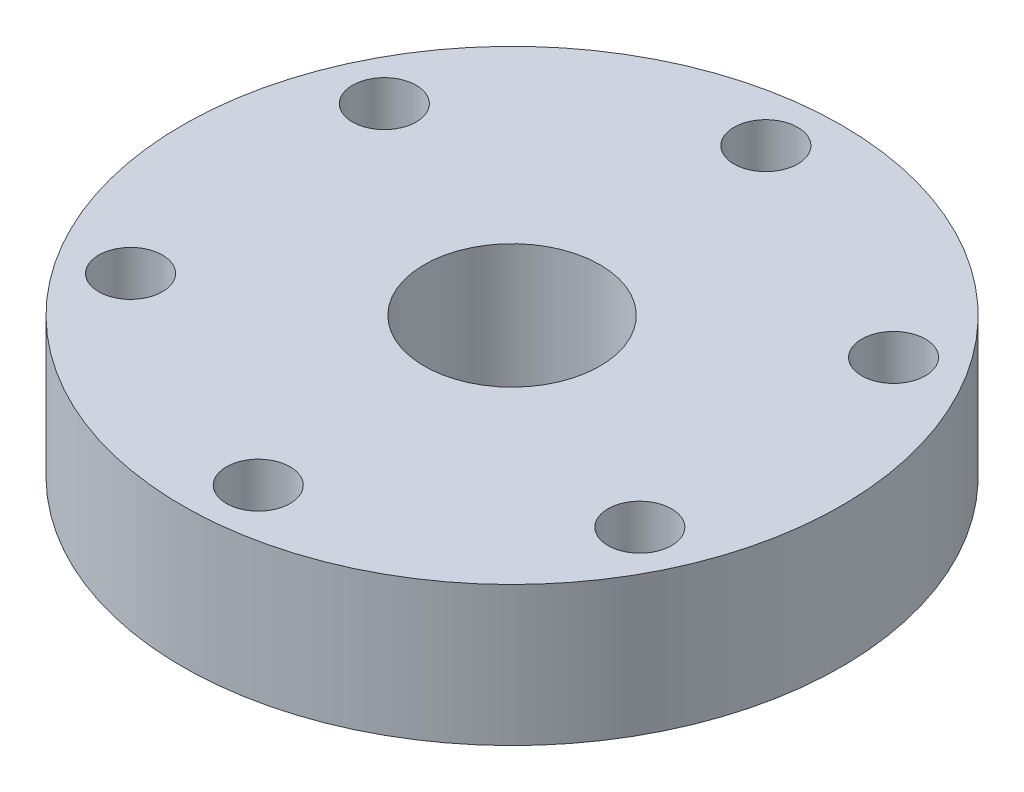
SolidWorks part; units mm, degrees
material "Aleación 6061"
ref_plane "Alzado" through (0, 0, 0) normal (0, 0, 1) x (1, 0, 0)
ref_plane "Planta" through (0, 0, 0) normal (0, 1, 0) x (1, 0, 0)
ref_plane "Vista lateral" through (0, 0, 0) normal (1, 0, 0) x (0, 0, -1)
sketch "Croquis1" plane through (0, 0, 0) normal (0, 1, 0) x (1, 0, 0)
  circle A0 centre (152.4, -336.55) radius 15
  dimension "D1" = 30
  dimension "D2" = 152.4
  dimension "D3" = 336.55
extrude "Disco" add sketch "Croquis1" along normal blind 6.35 from offset 3.175
sketch "Croquis2" plane through (0, 0, 0) normal (0, 1, 0) x (1, 0, 0)
  circle A0 centre (163.654, -341.9904) radius 1.45
  circle A1 centre (153.3155, -349.0164) radius 1.45
  circle A2 centre (142.0615, -343.576) radius 1.45
  circle A3 centre (141.146, -331.1096) radius 1.45
  circle A4 centre (151.4845, -324.0836) radius 1.45
  circle A5 centre (162.7385, -329.524) radius 1.45
  circle A6 centre (152.4, -336.55) radius 4
  dimension "D1" = 2.9
  dimension "D2" = 2.9
  dimension "D3" = 2.9
  dimension "D4" = 2.9
  dimension "D5" = 2.9
  dimension "D6" = 2.9
  dimension "D7" = 8
  dimension "D8" = 163.654
  dimension "D9" = 341.9904
  dimension "D10" = 153.3155
  dimension "D11" = 349.0164
  dimension "D12" = 142.0615
  dimension "D13" = 343.576
  dimension "D14" = 141.146
  dimension "D15" = 331.1096
  dimension "D16" = 151.4845
  dimension "D17" = 324.0836
  dimension "D18" = 162.7385
  dimension "D19" = 329.524
  dimension "D20" = 152.4
  dimension "D21" = 336.55
extrude "Barrenos" cut sketch "Croquis2" along normal blind 6.35 from offset 3.175
